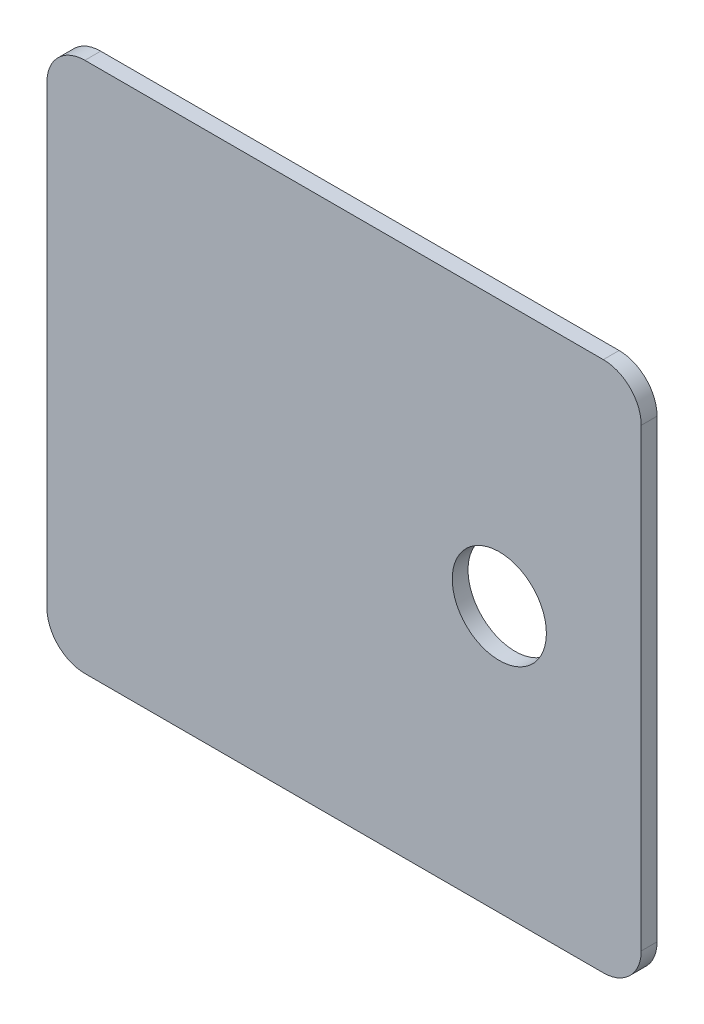
SolidWorks part; units mm, degrees
ref_plane "Alzado" through (0, 0, 0) normal (0, 0, 1) x (1, 0, 0)
ref_plane "Planta" through (0, 0, 0) normal (0, 1, 0) x (1, 0, 0)
ref_plane "Vista lateral" through (0, 0, 0) normal (1, 0, 0) x (0, 0, -1)
sketch "Croquis1" plane through (0, 0, 0) normal (0, 0, 1) x (1, 0, 0)
  line L0 (6.65, 45.25) -> (6.65, 12.25) construction
  line L1 (-64.9, 70.75) -> (29.1, 70.75)
  line L2 (-64.9, 70.75) -> (-64.9, -13.25)
  line L3 (-64.9, -13.25) -> (29.1, -13.25)
  line L4 (29.1, 70.75) -> (29.1, -13.25)
  line L6 (9.3, 12.25) -> (4, 12.25) construction
  circle A0 centre (6.65, 28.75) radius 7.4456
  point P16 (6.65, 12.25)
extrude "Saliente-Extruir1" add sketch "Croquis1" along normal blind 2.5 contours L1 L4 L3 L2
fillet "Redondeo1" radius 6 4 edges at (-64.9, 70.75, 1.25) (29.1, 70.75, 1.25) (29.1, -13.25, 1.25) (-64.9, -13.25, 1.25)
